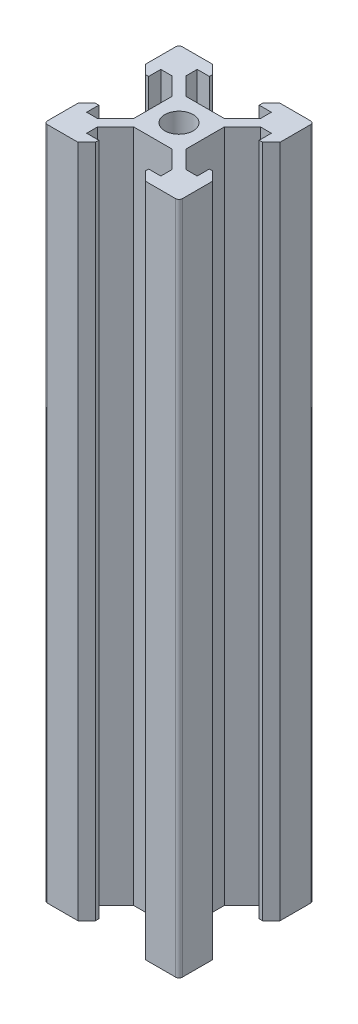
SolidWorks part; units mm, degrees
ref_plane "Front Plane" through (0, 0, 0) normal (0, 0, 1) x (1, 0, 0)
ref_plane "Top Plane" through (0, 0, 0) normal (0, 1, 0) x (1, 0, 0)
ref_plane "Right Plane" through (0, 0, 0) normal (1, 0, 0) x (0, 0, -1)
sketch "Sketch2" plane through (0, 0, 0) normal (0, 1, 0) x (1, 0, 0)
  line L1 (10, -10) -> (-10, -10)
  line L2 (10, -10) -> (10, 10)
  line L3 (10, 10) -> (-10, 10)
  line L4 (-10, -10) -> (-10, 10)
  line L5 (10, -10) -> (-10, 10) construction
  line L6 (10, 10) -> (-10, -10) construction
  circle A0 centre (0, 0) radius 2.1
  point P0 (0, 0)
  dimension "D3" = 4.2
  dimension "D1" = 20
  dimension "D2" = 20
extrude "Boss-Extrude1" add sketch "Sketch2" against normal blind 100
sketch "Sketch3" plane through (0, 0, 0) normal (0, 1, 0) x (1, 0, 0)
  line L0 (2.8483, -3.9) -> (5.5, -6.5517)
  line L1 (3.9, -3.9) -> (-3.9, -3.9)
  line L2 (3.9, -3.9) -> (3.9, 3.9)
  line L3 (3.9, 3.9) -> (-3.9, 3.9)
  line L4 (-3.9, -3.9) -> (-3.9, 3.9)
  line L5 (3.9, -3.9) -> (-3.9, 3.9) construction
  line L6 (3.9, 3.9) -> (-3.9, -3.9) construction
  line L7 (5.5, -6.5517) -> (5.5, -8.2)
  line L8 (5.5, -8.2) -> (3.7, -8.2)
  line L9 (3.7, 8.7) -> (5, 10)
  line L10 (3.7, -8.7) -> (5, -10)
  line L11 (-10, -10) -> (10, -10) construction
  line L12 (0, 9.1344) -> (0, -10.6406) construction
  line L13 (-12.5232, 0) -> (12.4953, 0) construction
  line L14 (10, -10) -> (10, 10) construction
  line L15 (5.5, 8.2) -> (3.7, 8.2)
  line L16 (5.5, 6.5517) -> (5.5, 8.2)
  line L17 (2.8483, 3.9) -> (5.5, 6.5517)
  line L18 (-3.7, -8.7) -> (-5, -10)
  line L19 (-5.5, -8.2) -> (-3.7, -8.2)
  line L20 (-5.5, -6.5517) -> (-5.5, -8.2)
  line L21 (-2.8483, -3.9) -> (-5.5, -6.5517)
  line L22 (-2.8483, 3.9) -> (-5.5, 6.5517)
  line L23 (-5.5, 6.5517) -> (-5.5, 8.2)
  line L24 (-5.5, 8.2) -> (-3.7, 8.2)
  line L25 (-3.7, 8.7) -> (-5, 10)
  line L26 (-10, 10) -> (10, -10) construction
  line L27 (-10, -10) -> (10, 10) construction
  line L28 (-8.7, -3.7) -> (-10, -5)
  line L29 (-8.2, -5.5) -> (-8.2, -3.7)
  line L30 (-6.5517, -5.5) -> (-8.2, -5.5)
  line L31 (-3.9, -2.8483) -> (-6.5517, -5.5)
  line L32 (8.7, -3.7) -> (10, -5)
  line L33 (8.2, -5.5) -> (8.2, -3.7)
  line L34 (6.5517, -5.5) -> (8.2, -5.5)
  line L35 (3.9, -2.8483) -> (6.5517, -5.5)
  line L36 (-3.9, 2.8483) -> (-6.5517, 5.5)
  line L37 (-6.5517, 5.5) -> (-8.2, 5.5)
  line L38 (-8.2, 5.5) -> (-8.2, 3.7)
  line L39 (-8.7, 3.7) -> (-10, 5)
  line L40 (3.9, 2.8483) -> (6.5517, 5.5)
  line L41 (6.5517, 5.5) -> (8.2, 5.5)
  line L42 (8.2, 5.5) -> (8.2, 3.7)
  line L43 (8.7, 3.7) -> (10, 5)
  line L44 (-5, 10) -> (-10, 10)
  line L45 (-10, 10) -> (-10, 5)
  line L46 (-10, -5) -> (-10, -10)
  line L47 (-10, -10) -> (-5, -10)
  line L48 (5, 10) -> (10, 10)
  line L49 (10, 10) -> (10, 5)
  line L50 (10, -5) -> (10, -10)
  line L51 (10, -10) -> (5, -10)
  line L52 (-8.7, 3.7) -> (-8.2, 3.7)
  line L53 (-8.7, -3.7) -> (-8.2, -3.7)
  line L54 (3.7, -8.2) -> (3.7, -8.7)
  line L55 (-3.7, -8.2) -> (-3.7, -8.7)
  line L56 (8.2, -3.7) -> (8.7, -3.7)
  line L57 (8.2, 3.7) -> (8.7, 3.7)
  line L58 (3.7, 8.7) -> (3.7, 8.2)
  line L59 (-3.7, 8.7) -> (-3.7, 8.2)
  point P0 (0, 0)
  line M27 (-10, 10) -> (-10, -10)
  line M28 (-10, -10) -> (10, -10)
  line M29 (10, -10) -> (10, 10)
  line M30 (10, 10) -> (-10, 10)
  dimension "D1" = 7.8
  dimension "D2" = 7.8
  dimension "D3" = 4.5
  dimension "D4" = 0.5
  dimension "D5" = 5
  dimension "D6" = 1.8
  dimension "D7" = 3.75
  dimension "D8" = 0.5
  dimension "D9" = 0.5
  dimension "D10" = 0.5
extrude "Cut-Extrude1" cut sketch "Sketch3" against normal through all contours L38 L39 L28 L29 L30 L31 L4 L36 L37 M27 | L1 L21 L20 L19 L18 L10 L8 L7 L0 M28 | L43 L42 L41 L40 L2 L35 L34 L33 L32 M29 | L25 L24 L23 L22 L3 L17 L16 L15 L9 M30
fillet "Fillet1" radius 0.5 4 edges at (-10, -50, 10) (-10, -50, -10) (10, -50, -10) (10, -50, 10)
